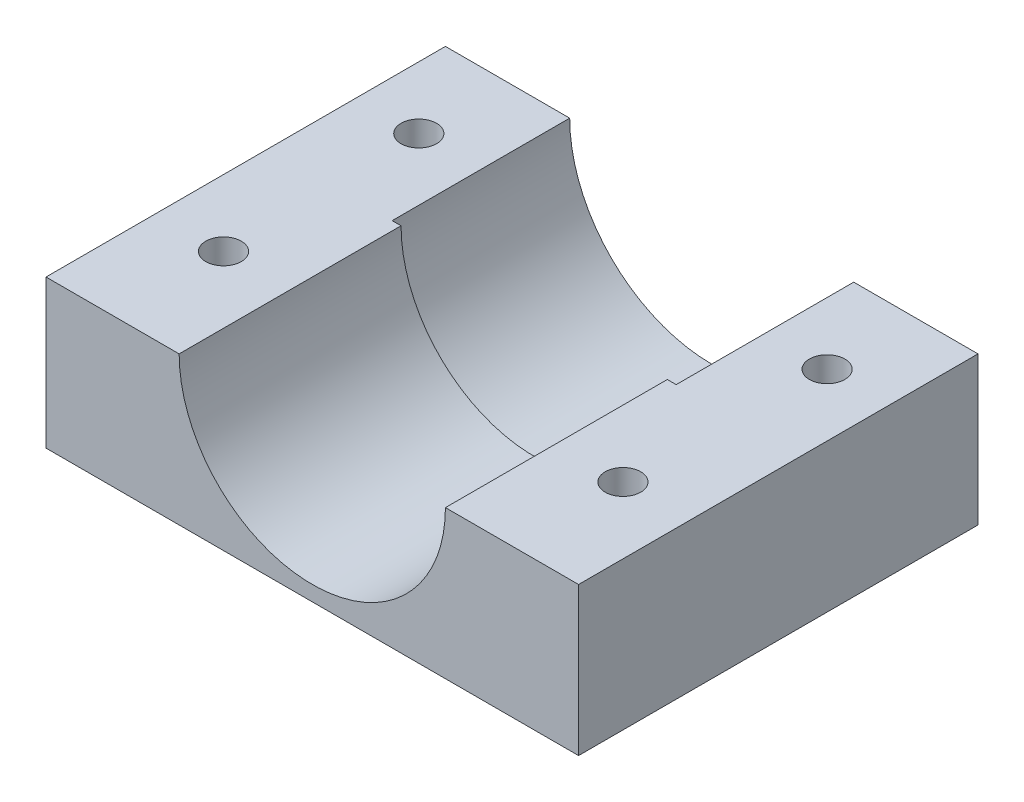
SolidWorks part; units mm, degrees
ref_plane "Plan de face" through (0, 0, 0) normal (0, 0, 1) x (1, 0, 0)
ref_plane "Plan de dessus" through (0, 0, 0) normal (0, 1, 0) x (1, 0, 0)
ref_plane "Plan de droite" through (0, 0, 0) normal (1, 0, 0) x (0, 0, -1)
sketch "Esquisse1" plane through (0, 0, 0) normal (0, 0, 1) x (1, 0, 0)
  line L0 (30, 0) -> (15, 0)
  line L1 (0, 0) -> (0, -16.6598) construction
  line L2 (30, -16.6968) -> (-30, -16.6968)
  line L3 (-30, -16.6968) -> (-30, 0)
  line L4 (30, -16.6968) -> (30, 0)
  line L5 (-15, 0) -> (-30, 0)
  arc A0 (-15, 0) -> (15, 0) centre (0, 0) ccw
  point P7 (-20, 0)
  point P10 (0, -16.6968)
  dimension "D1" = 30
  dimension "D3" = 10
extrude "BASE - 30 mm" add sketch "Esquisse1" along normal blind 25 contours A0 L0 L4 L2 L3 L5
sketch "Esquisse4" plane through (0, 0, 0) normal (0, 0, 1) x (1, 0, 0)
  line L0 (20, 0) -> (30, 0)
  line L1 (30, 0) -> (30, -16.6968)
  line L2 (30, -16.6968) -> (-30, -16.6968)
  line L3 (-30, -16.6968) -> (-30, 0)
  line L4 (-30, 0) -> (-20, 0)
  line L5 (20, 0) -> (16, 0)
  line L6 (-20, 0) -> (-16, 0)
  arc A0 (-16, 0) -> (16, 0) centre (0, 0) ccw
  dimension "D1" = 32
extrude "BASE - 32 mm" add sketch "Esquisse4" against normal blind 20
sketch "Esquisse5" plane through (0, -16.6968, 0) normal (0, -1, 0) x (1, 0, 0)
  line L1 (-30, 25) -> (30, -20) construction
  line L2 (30, -20) -> (30, 0) construction
  line L3 (30, 25) -> (30, -20) construction
  line L4 (30, 0) -> (-30, 0) construction
  line L5 (-30, 25) -> (-30, -20) construction
  line L7 (-30, -20) -> (-16, 0) construction
  line L8 (-16, -20) -> (-16, 0) construction
  line L9 (0, -37.5556) -> (0, 45.0246) construction
  line L10 (-15, 0) -> (-30, 25) construction
  circle A0 centre (-23, -10) radius 2
  circle A1 centre (-22.5, 12.5) radius 2
  circle A2 centre (22.5, 12.5) radius 2
  circle A3 centre (23, -10) radius 2
  point P20 (-23, -10)
  point P23 (-22.5, 12.5)
  dimension "D1" = 4
  dimension "D2" = 4
extrude "VIDE VIS" cut sketch "Esquisse5" against normal up to surface (16.6968 mm away) up to face at (-20.25, 0, 0)
